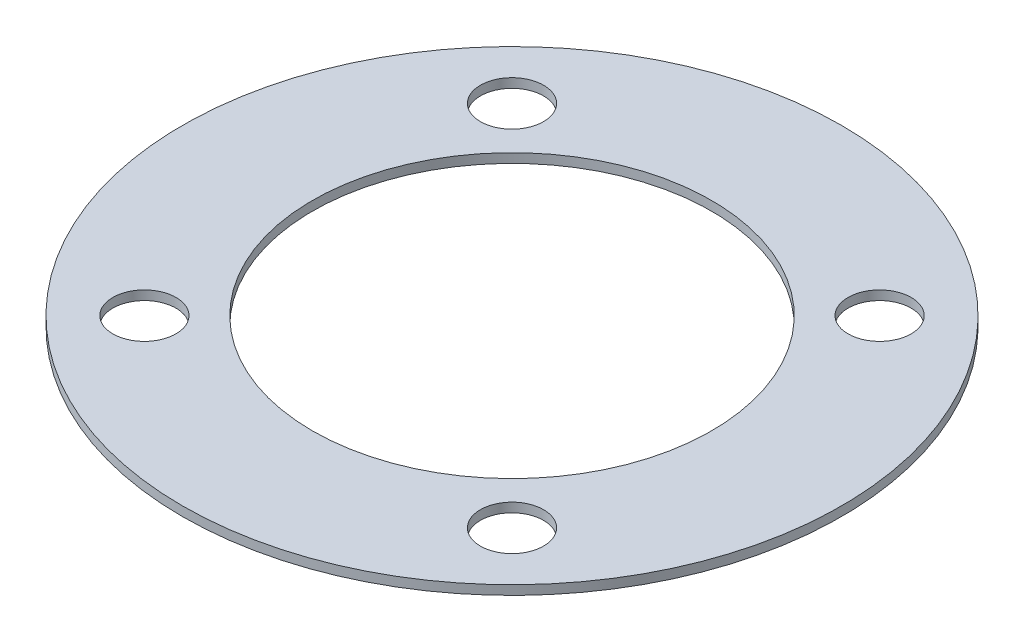
SolidWorks part; units mm, degrees
material "ｼﾘｺﾝ ｺﾞﾑ"
ref_plane "正面" through (0, 0, 0) normal (0, 0, 1) x (1, 0, 0)
ref_plane "平面" through (0, 0, 0) normal (0, 1, 0) x (1, 0, 0)
ref_plane "右側面" through (0, 0, 0) normal (1, 0, 0) x (0, 0, -1)
sketch "ｽｹｯﾁ1" plane through (0, 0, 0) normal (0, 1, 0) x (1, 0, 0)
  circle A0 centre (0, 0) radius 17.75
  dimension "D1" = 35.5
extrude "ﾎﾞｽ - 押し出し1" add sketch "ｽｹｯﾁ1" along normal blind 0.5
sketch "ｽｹｯﾁ2" plane through (0, 0.5, 0) normal (0, 1, 0) x (1, 0, 0)
  circle A0 centre (0, 0) radius 10.75
  dimension "D1" = 21.5
extrude "ｶｯﾄ - 押し出し1" cut sketch "ｽｹｯﾁ2" against normal through all
sketch "ｽｹｯﾁ4" plane through (0, 0.5, 0) normal (0, 1, 0) x (1, 0, 0)
  line L0 (-9.8995, 9.8995) -> (9.8995, -9.8995)
  line L1 (-9.8995, 9.8995) -> (9.8995, 9.8995)
  line L2 (-9.8995, 9.8995) -> (-9.8995, -9.8995)
  line L3 (-9.8995, -9.8995) -> (9.8995, -9.8995)
  line L4 (9.8995, 9.8995) -> (9.8995, -9.8995)
  line L5 (9.8995, 9.8995) -> (-9.8995, -9.8995)
  point P0 (-9.8995, 9.8995)
  point P1 (9.8995, -9.8995)
  point P2 (-9.8995, -9.8995)
  point P3 (9.8995, 9.8995)
  point P4 (0, 0)
  dimension "D1" = 14
hole_wizard "M3 すきま穴1" positions "ｽｹｯﾁ4" profile "ｽｹｯﾁ5" hole size "M3" standard "JIS" end condition through all
sketch "ｽｹｯﾁ5" plane through (-9.8995, 0.5, -9.8995) normal (1, 0, 0) x (0, 0, 1)
  line L0 (0, 0) -> (0, 0.5)
  line L1 (0, 0.5) -> (1.7, 0.5)
  line L2 (1.7, 0.5) -> (1.7, 0)
  line L5 (1.7, 0) -> (0, 0)
  line L11 (0, -6.35) -> (0, 107.95) construction
  dimension "通し穴の直径" = 3.4
  dimension "通し穴の深さ" = 0.5
